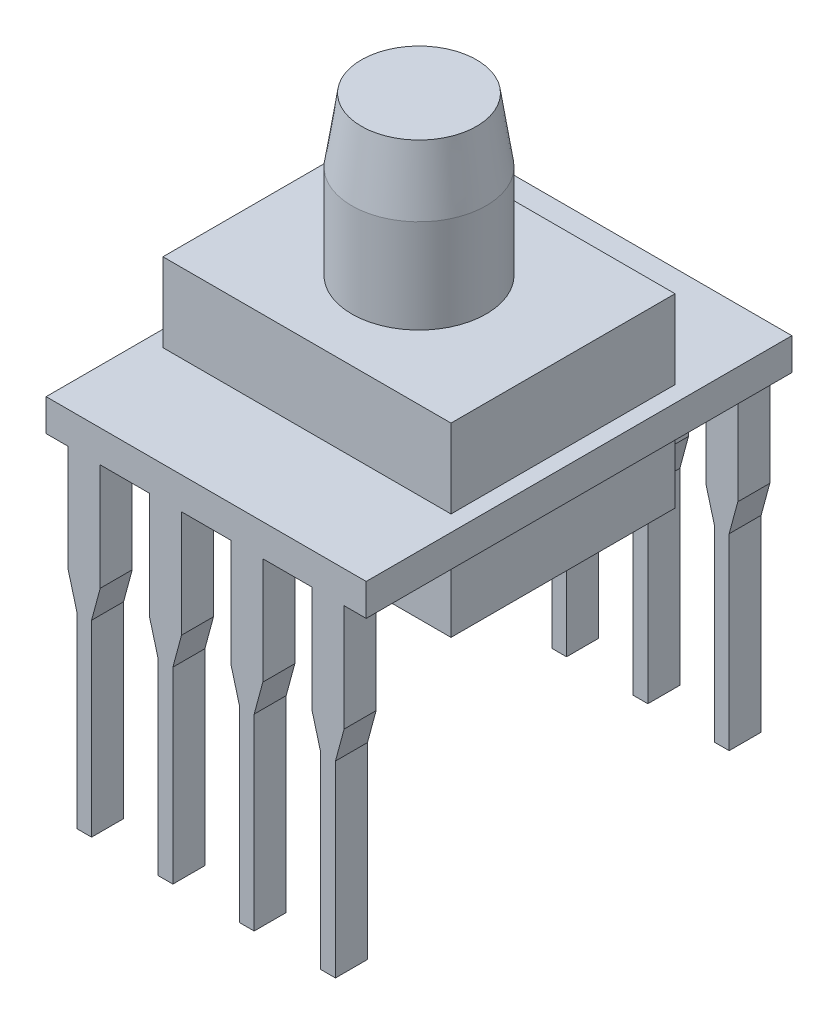
SolidWorks part; units mm, degrees
ref_plane "Front Plane" through (0, 0, 0) normal (0, 0, 1) x (1, 0, 0)
ref_plane "Top Plane" through (0, 0, 0) normal (0, 1, 0) x (1, 0, 0)
ref_plane "Right Plane" through (0, 0, 0) normal (1, 0, 0) x (0, 0, -1)
sketch "Sketch1" plane through (0, 0, 0) normal (0, 1, 0) x (1, 0, 0)
  line L1 (-5, -6.65) -> (5, -6.65)
  line L2 (-5, -6.65) -> (-5, 6.65)
  line L3 (-5, 6.65) -> (5, 6.65)
  line L4 (5, -6.65) -> (5, 6.65)
  line L5 (-5, -6.65) -> (5, 6.65) construction
  line L6 (-5, 6.65) -> (5, -6.65) construction
  point P0 (0, 0)
  dimension "D1" = 10
  dimension "D2" = 13.3
extrude "Boss-Extrude1" add sketch "Sketch1" along normal blind 1
sketch "Sketch2" plane through (0, 1, 0) normal (0, 1, 0) x (1, 0, 0)
  line L1 (4.5, -3.5) -> (-4.5, -3.5)
  line L2 (4.5, -3.5) -> (4.5, 3.5)
  line L3 (4.5, 3.5) -> (-4.5, 3.5)
  line L4 (-4.5, -3.5) -> (-4.5, 3.5)
  line L5 (4.5, -3.5) -> (-4.5, 3.5) construction
  line L6 (4.5, 3.5) -> (-4.5, -3.5) construction
  point P0 (0, 0)
  dimension "D1" = 7
  dimension "D2" = 9
extrude "Boss-Extrude2" add sketch "Sketch2" along normal blind 2.46 and the other way blind 3.34
sketch "Sketch3" plane through (0, 3.46, 0) normal (0, 1, 0) x (1, 0, 0)
  circle A0 centre (0, 0) radius 2.1
  dimension "D1" = 4.2
extrude "Boss-Extrude3" add sketch "Sketch3" along normal blind 4.93
chamfer "Chamfer1" distance 2 distance2 0.3 1 edges at (0, 8.39, 2.1)
sketch "Sketch5" plane through (0, 0, 6.65) normal (0, 0, 1) x (1, 0, 0)
  line L0 (-5, 1) -> (5, 1) construction
  line L1 (-4.31, 1) -> (-4.31, -3.34)
  line L2 (-4.31, -3.34) -> (-4.04, -4.34)
  line L3 (-4.04, -4.34) -> (-4.04, -10.21)
  line L4 (-4.04, -10.21) -> (-3.58, -10.21)
  line L5 (-3.58, -10.21) -> (-3.58, -4.34)
  line L6 (-3.58, -4.34) -> (-3.31, -3.34)
  line L7 (-3.31, -3.34) -> (-3.31, 1)
  line L8 (-3.31, 1) -> (-4.31, 1)
  line L9 (-3.81, 1) -> (-3.81, -49999) construction
  line L10 (0, 0) -> (0, -50000) construction
  line L11 (-5, 0) -> (5, 0) construction
  line L12 (-1.77, 1) -> (-1.77, -3.34)
  line L13 (-1.77, -3.34) -> (-1.5, -4.34)
  line L14 (-1.5, -4.34) -> (-1.5, -10.21)
  line L15 (-1.5, -10.21) -> (-1.04, -10.21)
  line L16 (-1.04, -10.21) -> (-1.04, -4.34)
  line L17 (-1.04, -4.34) -> (-0.77, -3.34)
  line L18 (-0.77, -3.34) -> (-0.77, 1)
  line L19 (-0.77, 1) -> (-1.77, 1)
  line L20 (0.77, 1) -> (0.77, -3.34)
  line L21 (0.77, -3.34) -> (1.04, -4.34)
  line L22 (1.04, -4.34) -> (1.04, -10.21)
  line L23 (1.04, -10.21) -> (1.5, -10.21)
  line L24 (1.5, -10.21) -> (1.5, -4.34)
  line L25 (1.5, -4.34) -> (1.77, -3.34)
  line L26 (1.77, -3.34) -> (1.77, 1)
  line L27 (1.77, 1) -> (0.77, 1)
  line L28 (3.31, 1) -> (3.31, -3.34)
  line L29 (3.31, -3.34) -> (3.58, -4.34)
  line L30 (3.58, -4.34) -> (3.58, -10.21)
  line L31 (3.58, -10.21) -> (4.04, -10.21)
  line L32 (4.04, -10.21) -> (4.04, -4.34)
  line L33 (4.04, -4.34) -> (4.31, -3.34)
  line L34 (4.31, -3.34) -> (4.31, 1)
  line L35 (4.31, 1) -> (3.31, 1)
  line L36 (-4.5, -2.34) -> (4.5, -2.34) construction
  point P12 (-3.81, 1)
  point P17 (0, 0)
  point P18 (0, 0)
  point P43 (0, 0)
  dimension "D1" = 0.46
  dimension "D2" = 1
  dimension "D4" = 2.54
  dimension "D5" = 11.21
  dimension "D6" = 1
  dimension "D7" = 1
  dimension "D3" = 4
extrude "Boss-Extrude4" add sketch "Sketch5" against normal blind 1
mirror "Mirror1" about plane through (0, 0, 0) normal (0, 0, 1) of "Boss-Extrude4"
